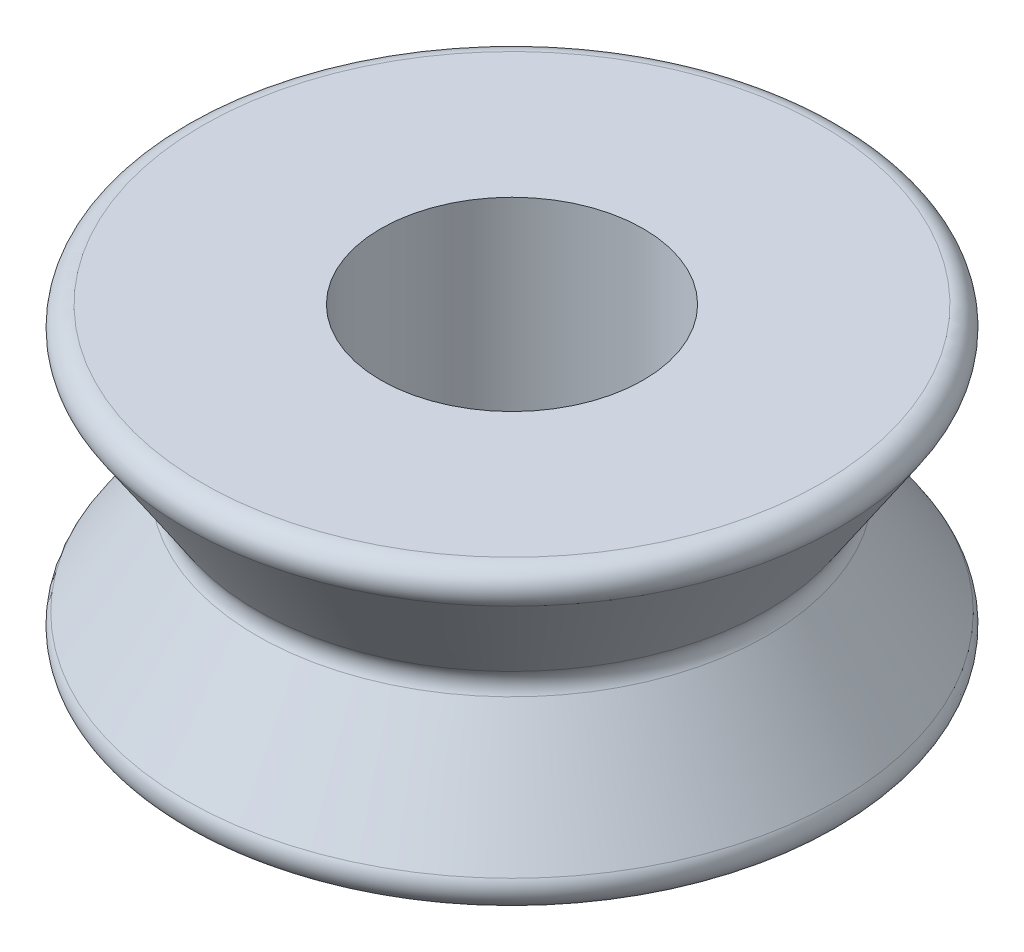
SolidWorks part; units mm, degrees
ref_plane "Plan de face" through (0, 0, 0) normal (0, 0, 1) x (1, 0, 0)
ref_plane "Plan de dessus" through (0, 0, 0) normal (0, 1, 0) x (1, 0, 0)
ref_plane "Plan de droite" through (0, 0, 0) normal (1, 0, 0) x (0, 0, -1)
sketch "Esquisse2" plane through (0, 0, 0) normal (0, 0, 1) x (1, 0, 0)
  line L0 (-7, 3) -> (-5, 0)
  line L1 (-7, 3) -> (0, 3)
  line L2 (-7, 3) -> (-7, -3) construction
  line L3 (-7, -3) -> (0, -3)
  line L4 (0, 0) -> (-5, 0) construction
  line L5 (0, 3) -> (0, -3)
  line L7 (-5, 0) -> (-7, -3)
  line L10 (0, 3) -> (0, -3) construction
  point P0 (0, 0)
  dimension "D1" = 5
  dimension "D2" = 6
  dimension "D3" = 7
revolve "Révolution1" add sketch "Esquisse2" angle 360 about L5
fillet "Congé1" radius 0.4 3 edges at (-7, 3, 0) (-5, 0, 0) (-7, -3, 0)
hole_wizard "Dégagement M51" positions "Esquisse4" profile "Esquisse3" hole size "M5" standard "Din" end condition through all
sketch "Esquisse4" plane through (0, 3, 0) normal (0, 1, 0) x (1, 0, 0)
  point P0 (0, 0)
sketch "Esquisse3" plane through (0, 3, 0) normal (1, 0, 0) x (0, 0, 1)
  line L0 (0, 0) -> (0, 6)
  line L1 (0, 6) -> (2.65, 6)
  line L2 (2.65, 6) -> (2.65, 0)
  line L5 (2.65, 0) -> (0, 0)
  line L11 (0, -6.35) -> (0, 107.95) construction
  dimension "Diamètre du perçage jusqu'au prochain" = 5.3
  dimension "Profondeur du perçage jusqu'au prochain" = 6
